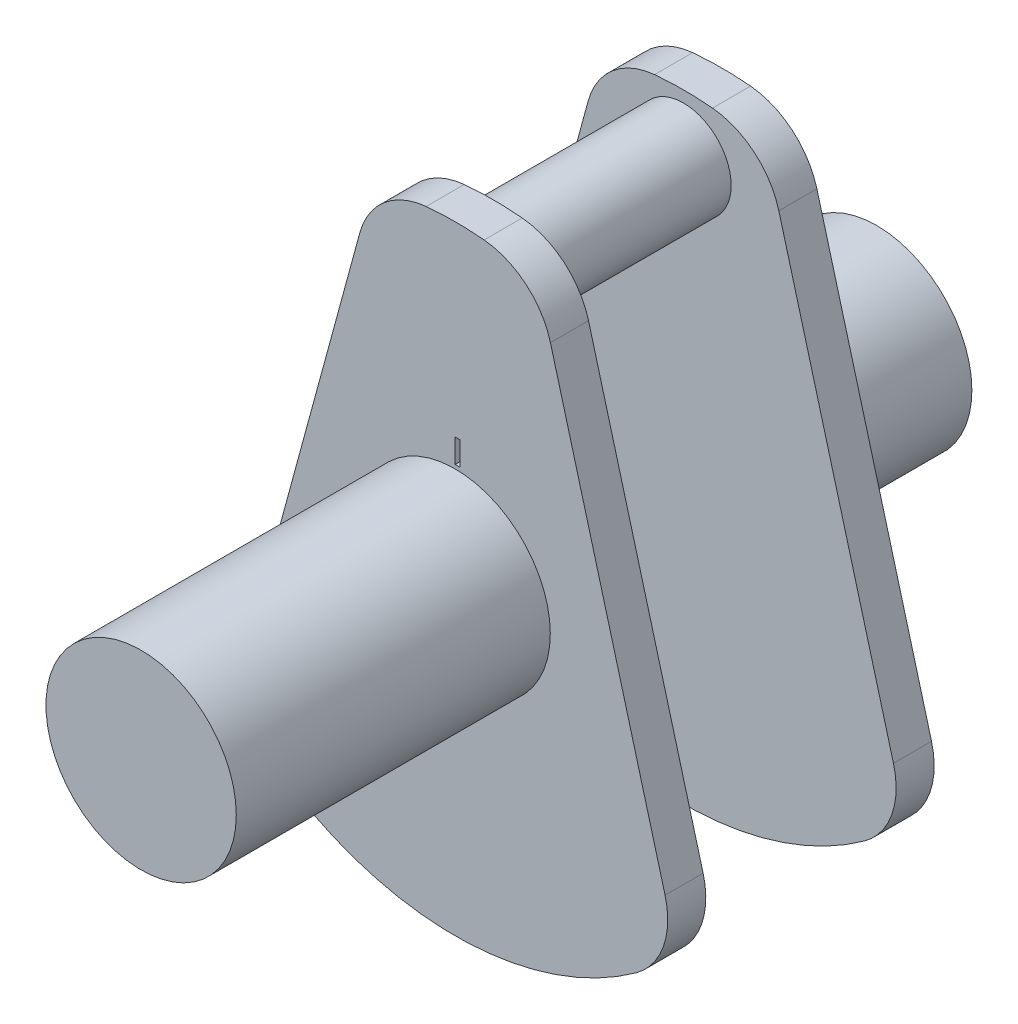
SolidWorks part; units mm, degrees
ref_plane "Front Plane" through (0, 0, 0) normal (0, 0, 1) x (1, 0, 0)
ref_plane "Top Plane" through (0, 0, 0) normal (0, 1, 0) x (1, 0, 0)
ref_plane "Right Plane" through (0, 0, 0) normal (1, 0, 0) x (0, 0, -1)
sketch "Sketch2" plane through (0, 0, 0) normal (0, 0, 1) x (1, 0, 0)
  line L0 (0, 6.5) -> (0, -6.5) construction
  line L1 (-2.0028, 5.2986) -> (-4.4119, -3.5528)
  line L2 (2.0028, 5.2986) -> (4.4119, -3.5528)
  arc A0 (-3.8045, -5.2703) -> (3.8045, -5.2703) centre (0, 0) ccw
  arc A1 (0.6089, 6.4714) -> (-0.6089, 6.4714) centre (0, 0) ccw
  arc A2 (2.0028, 5.2986) -> (0.6089, 6.4714) centre (0.459, 4.8785) ccw
  arc A3 (-0.6089, 6.4714) -> (-2.0028, 5.2986) centre (-0.459, 4.8785) ccw
  arc A4 (3.8045, -5.2703) -> (4.4119, -3.5528) centre (2.868, -3.973) ccw
  arc A5 (-3.8045, -5.2703) -> (-4.4119, -3.5528) centre (-2.868, -3.973) cw
  point P10 (1.7405, 6.2626)
  point P13 (-1.7405, 6.2626)
  point P16 (4.6742, -4.5168)
  point P19 (-4.6742, -4.5168)
  dimension "D1" = 13
  dimension "D4" = 1.6
  dimension "D5" = 1.6
  dimension "D2" = 30.45
  dimension "D3" = 0.918
extrude "Boss-Extrude1" add sketch "Sketch2" along normal blind 0.8
sketch "Sketch3" plane through (0, 0, 0.8) normal (0, 0, 1) x (1, 0, 0)
  line L0 (0, 6.5) -> (0, 5.259) construction
  arc A0 (0.6089, 6.4714) -> (-0.6089, 6.4714) centre (0, 0) ccw construction
  circle A1 centre (0, 5.259) radius 1
  dimension "D1" = 2
  dimension "D2" = 5.259
extrude "Boss-Extrude2" add sketch "Sketch3" along normal blind 2
sketch "Sketch4" plane through (0, 0, 0) normal (0, 0, -1) x (-1, 0, 0)
  circle A0 centre (0, 0) radius 2
  dimension "D1" = 4
extrude "Boss-Extrude3" add sketch "Sketch4" along normal blind 3.26
mirror "Mirror1" about plane through (0, 5.259, 2.8) normal (0, 0, 1) of bodies 103
sketch "Sketch8" plane through (0, 0, 8.86) normal (0, 0, 1) x (1, 0, 0)
  circle A1 centre (0, 0) radius 2
  circle A2 centre (0, 0) radius 2
  dimension "D1" = 0
extrude "Boss-Extrude4" add sketch "Sketch8" along normal blind 3.34
sketch "Sketch9" plane through (0, 0, 5.6) normal (0, 0, 1) x (1, 0, 0)
  line L0 (0, 0) -> (0, 6.407) construction
  line L2 (0, 2.08) -> (0.1, 2.08)
  line L3 (0, 2.08) -> (0, 2.58)
  line L4 (0, 2.58) -> (0.1, 2.58)
  line L5 (0.1, 2.08) -> (0.1, 2.58)
  dimension "D1" = 0.5
  dimension "D2" = 0.1
extrude "Cut-Extrude1" cut sketch "Sketch9" against normal blind 0.1
